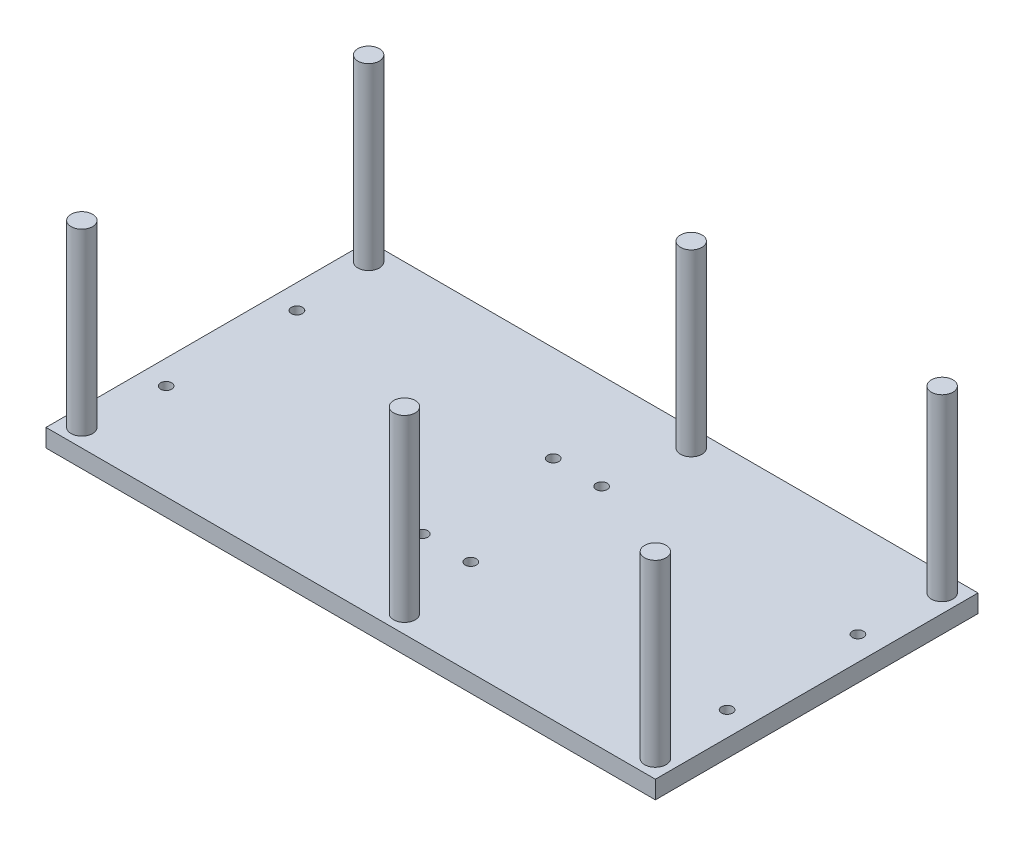
SolidWorks part; units mm, degrees
ref_plane "Front Plane" through (0, 0, 0) normal (0, 0, 1) x (1, 0, 0)
ref_plane "Top Plane" through (0, 0, 0) normal (0, 1, 0) x (1, 0, 0)
ref_plane "Right Plane" through (0, 0, 0) normal (1, 0, 0) x (0, 0, -1)
sketch "Sketch1" plane through (0, 0, 0) normal (0, 1, 0) x (1, 0, 0)
  line L1 (0, 0) -> (170, 0)
  line L2 (0, 0) -> (0, 90)
  line L3 (0, 90) -> (170, 90)
  line L4 (170, 0) -> (170, 90)
  dimension "D1" = 170
  dimension "D2" = 90
extrude "Boss-Extrude1" add sketch "Sketch1" along normal blind 5
sketch "Sketch2" plane through (0, 5, 0) normal (0, 1, 0) x (1, 0, 0)
  line L0 (5, 90) -> (5, 85) construction
  line L1 (170, 90) -> (0, 90) construction
  line L2 (0, 90) -> (0, 0) construction
  line L3 (85, 90) -> (85, 0) construction
  line L4 (0, 0) -> (170, 0) construction
  line L5 (0, 45) -> (170, 45) construction
  line L6 (170, 0) -> (170, 90) construction
  line L7 (5, 85) -> (165, 85) construction
  circle A0 centre (5, 85) radius 3
  circle A1 centre (5, 5) radius 3
  circle A2 centre (165, 5) radius 3
  circle A3 centre (165, 85) radius 3
  circle A4 centre (95, 85) radius 3
  circle A5 centre (95, 5) radius 3
  dimension "D2" = 70
  dimension "D1" = 5
extrude "Boss-Extrude2" add sketch "Sketch2" along normal blind 50
sketch "Sketch3" plane through (0, 0, 0) normal (0, -1, 0) x (1, 0, 0)
  line L0 (6.75, 0) -> (6.75, -90) construction
  line L1 (0, 0) -> (170, 0) construction
  line L2 (170, -90) -> (0, -90) construction
  line L3 (6.75, -26.75) -> (78.25, -26.75) construction
  line L4 (78.25, -26.75) -> (78.25, -63.25) construction
  line L5 (78.25, -63.25) -> (4.977, -63.25) construction
  line L7 (85, 0) -> (85, -90) construction
  line L8 (0, -90) -> (0, 0) construction
  circle A0 centre (6.75, -26.75) radius 1.55
  circle A2 centre (78.25, -26.75) radius 1.55
  circle A3 centre (78.25, -63.25) radius 1.55
  circle A4 centre (6.75, -63.25) radius 1.55
  circle A5 centre (163.25, -63.25) radius 1.55
  circle A6 centre (91.75, -63.25) radius 1.55
  circle A7 centre (91.75, -26.75) radius 1.55
  circle A8 centre (163.25, -26.75) radius 1.55
  dimension "D1" = 71.5
  dimension "D3" = 6.75
  dimension "D2" = 36.5
  dimension "D4" = 26.75
extrude "Cut-Extrude1" cut sketch "Sketch3" against normal blind 50
